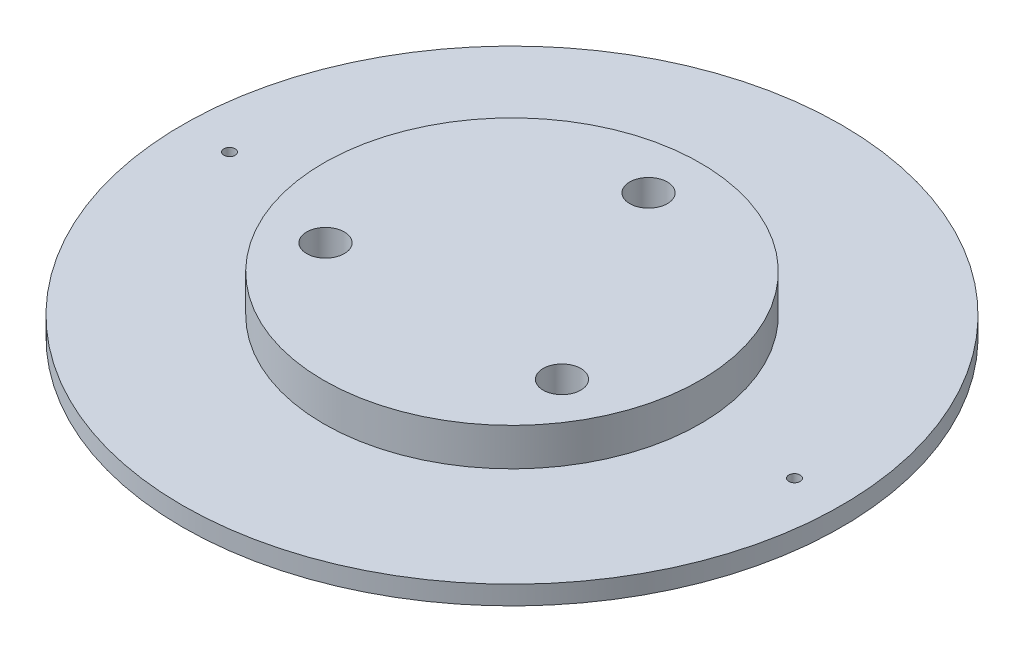
SolidWorks part; units mm, degrees
ref_plane "前基準面" through (0, 0, 0) normal (0, 0, 1) x (1, 0, 0)
ref_plane "上基準面" through (0, 0, 0) normal (0, 1, 0) x (1, 0, 0)
ref_plane "右基準面" through (0, 0, 0) normal (1, 0, 0) x (0, 0, -1)
sketch "草圖1" plane through (0, 0, 0) normal (0, 1, 0) x (1, 0, 0)
  line L0 (0, 0) -> (0, 72.5) construction
  line L1 (0, 0) -> (-62.7868, -36.25) construction
  line L2 (0, 0) -> (62.7868, -36.25) construction
  circle A0 centre (0, 0) radius 72.5 construction
  circle A1 centre (0, 72.5) radius 10
  circle A2 centre (62.7868, -36.25) radius 10
  circle A3 centre (-62.7868, -36.25) radius 10
  circle A4 centre (0, 0) radius 40 construction
  circle A5 centre (0, 0) radius 100
  dimension "D3" = 145
  dimension "D4" = 20
  dimension "D5" = 80
  dimension "D6" = 200
  dimension "D1" = 120
  dimension "D2" = 120
extrude "填料-伸長1" add sketch "草圖1" along normal blind 20
sketch "草圖2" plane through (0, 0, 0) normal (0, -1, 0) x (1, 0, 0)
  line L0 (-150, 0) -> (150, 0) construction
  circle A0 centre (-150, 0) radius 3
  circle A1 centre (150, 0) radius 3
  circle A2 centre (0, 0) radius 175
  point P3 (0, 0)
  dimension "D2" = 6
  dimension "D3" = 350
  dimension "D1" = 300
extrude "填料-伸長2" add sketch "草圖2" along normal blind 10
